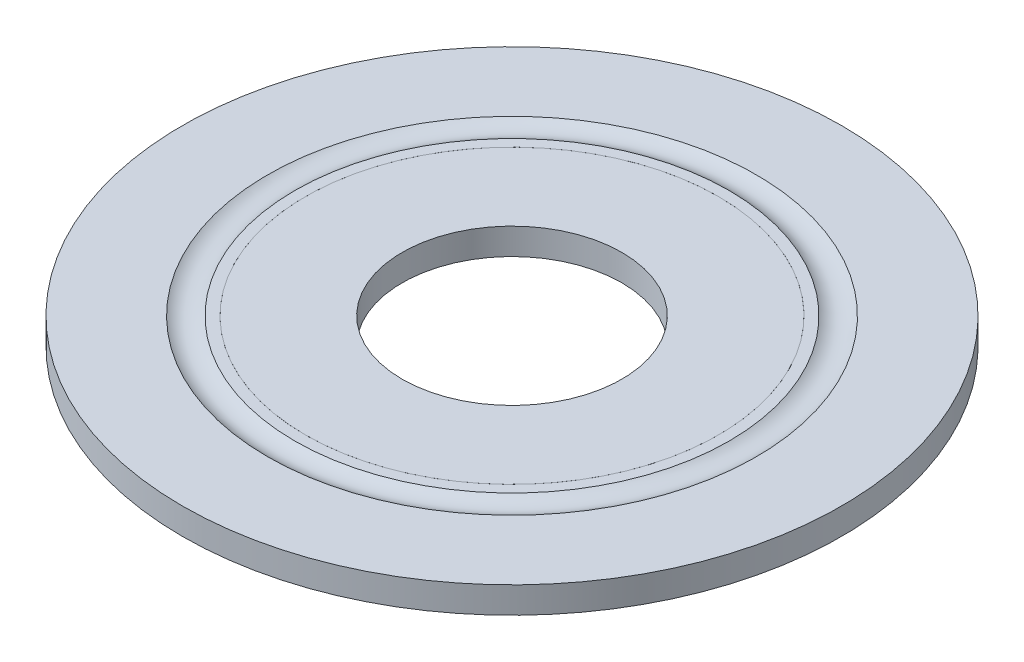
SolidWorks part; units mm, degrees
ref_plane "Front Plane" through (0, 0, 0) normal (0, 0, 1) x (1, 0, 0)
ref_plane "Top Plane" through (0, 0, 0) normal (0, 1, 0) x (1, 0, 0)
ref_plane "Right Plane" through (0, 0, 0) normal (1, 0, 0) x (0, 0, -1)
ref_plane "Plane1" through (0, 0, 0) normal (0, 0, -1) x (-1, 0, 0)
sketch "Sketch1" plane through (0, 0, 0) normal (0, 0, -1) x (-1, 0, 0)
  line L0 (-59, 0.8724) -> (-47, 0.8724)
  line L1 (-46, 1.8724) -> (-46, 5.8724)
  line L2 (-46, 5.8724) -> (-47, 6.8724)
  line L3 (-47, 6.8724) -> (-49.4043, 6.8724)
  line L4 (-55.5957, 6.8724) -> (-59, 6.8724)
  line L5 (-59, 6.8724) -> (-60, 5.8724)
  line L6 (-60, 5.8724) -> (-60, 1.8724)
  line L7 (0, 0) -> (0, 6.8724) construction
  arc A0 (-47, 0.8724) -> (-46, 1.8724) centre (-47, 1.8724) ccw
  arc A1 (-49.4043, 6.8724) -> (-55.5957, 6.8724) centre (-52.5, 11) cw
  arc A2 (-60, 1.8724) -> (-59, 0.8724) centre (-59, 1.8724) ccw
  dimension "D1" = 5.1595
  dimension "D2" = 14
  dimension "D3" = 6.1914
  dimension "D4" = 6
revolve "Revolve1" add sketch "Sketch1" angle 360 about L7
sketch "Sketch2" plane through (0, 0.8724, 0) normal (0, -1, 0) x (1, 0, 0)
  circle A0 centre (0, 0) radius 75
  circle A2 centre (0, 0) radius 46.9929
  circle A3 centre (0, 0) radius 59
extrude "Boss-Extrude1" add sketch "Sketch2" against normal blind 6 contours A0 A3 | A2
sketch "Sketch7" plane through (0, 0.8724, 0) normal (0, -1, 0) x (1, 0, 0)
  circle A1 centre (0, 0) radius 15
extrude "Cut-Extrude3" [suppressed] cut sketch "Sketch7" against normal blind 3
sketch "Sketch8" plane through (0, 6.8724, 0) normal (0, 1, 0) x (1, 0, 0)
  circle A0 centre (0, 0) radius 25
  dimension "D1" = 50
extrude "Cut-Extrude4" cut sketch "Sketch8" against normal blind 6
